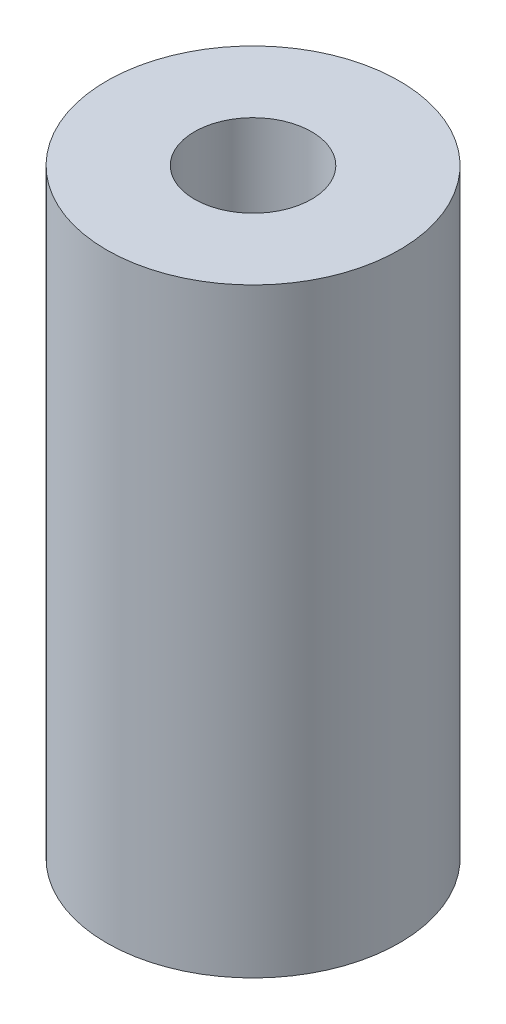
SolidWorks part; units mm, degrees
ref_plane "Спереди" through (0, 0, 0) normal (0, 0, 1) x (1, 0, 0)
ref_plane "Сверху" through (0, 0, 0) normal (0, 1, 0) x (1, 0, 0)
ref_plane "Справа" through (0, 0, 0) normal (1, 0, 0) x (0, 0, -1)
sketch "Эскиз1" plane through (0, 0, 0) normal (0, 1, 0) x (1, 0, 0)
  circle A0 centre (0, 0) radius 5
  circle A1 centre (0, 0) radius 2
  dimension "D1" = 10
  dimension "D2" = 4
extrude "Бобышка-Вытянуть1" add sketch "Эскиз1" along normal blind 20.5
